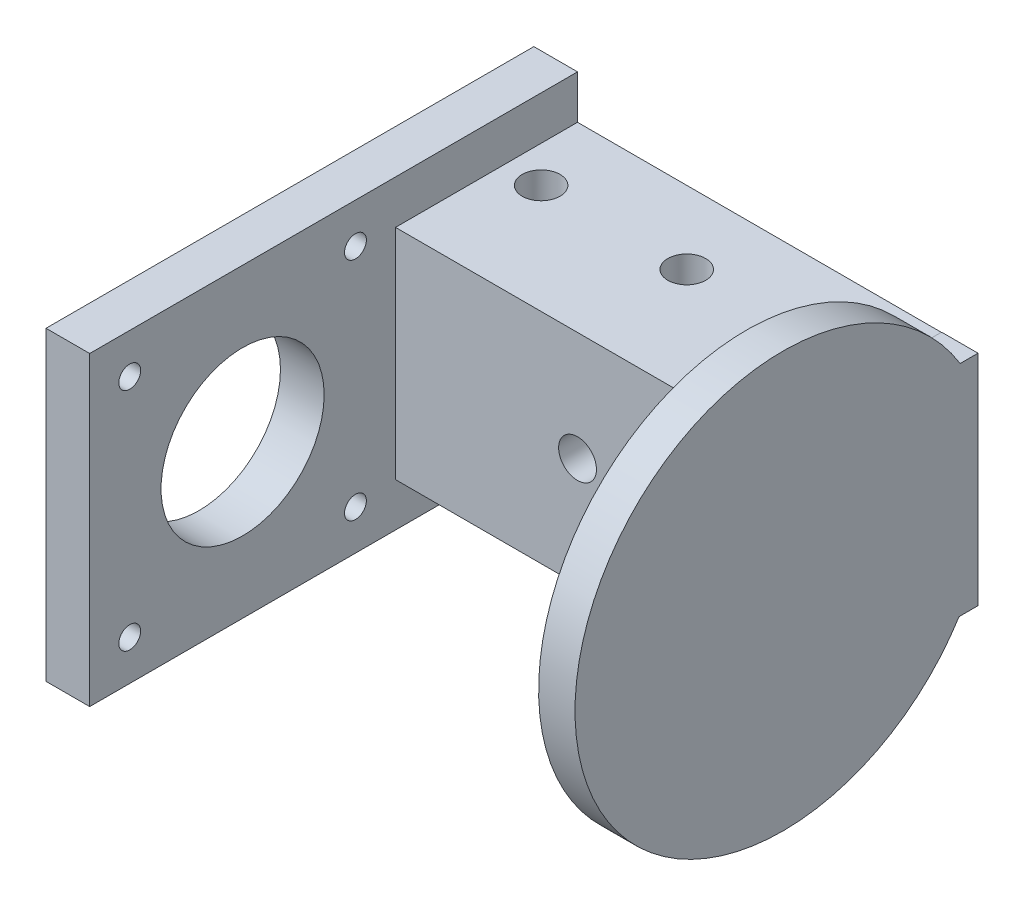
SolidWorks part; units mm, degrees
ref_plane "Front Plane" through (0, 0, 0) normal (0, 0, 1) x (1, 0, 0)
ref_plane "Top Plane" through (0, 0, 0) normal (0, 1, 0) x (1, 0, 0)
ref_plane "Right Plane" through (0, 0, 0) normal (1, 0, 0) x (0, 0, -1)
ref_plane "Plane1" through (45.0281, 0, 0) normal (1, 0, 0) x (0, 0, -1)
sketch "Sketch1" plane through (45.0281, 0, 0) normal (1, 0, 0) x (0, 0, -1)
  line L0 (-47, 0) -> (20, 0)
  line L1 (20, 0) -> (20, 42)
  line L2 (20, 42) -> (-47, 42)
  line L3 (-47, 42) -> (-47, 0)
  dimension "D1" = 67
  dimension "D2" = 42
  dimension "D3" = 20
extrude "Boss-Extrude1" add sketch "Sketch1" against normal blind 6
sketch "Sketch2" plane through (45.0281, 0, 0) normal (1, 0, 0) x (0, 0, -1)
  line L0 (20, 36) -> (20, 6)
  line L1 (20, 6) -> (-5, 6)
  line L2 (-5, 6) -> (-5, 36)
  line L3 (-5, 36) -> (20, 36)
  dimension "D1" = 25
extrude "Boss-Extrude2" add sketch "Sketch2" along normal blind 50
sketch "Sketch3" plane through (39.0281, 0, 0) normal (-1, 0, 0) x (0, 0, 1)
  line L0 (-20, 31) -> (-20, 11)
  line L1 (-20, 11) -> (0, 11)
  line L2 (0, 11) -> (0, 31)
  line L3 (0, 31) -> (-20, 31)
extrude "Cut-Extrude1" cut sketch "Sketch3" against normal through all
sketch "Sketch14" plane through (45.0281, 0, 0) normal (1, 0, 0) x (0, 0, -1)
  line L0 (-5, 36) -> (-5, 6) construction
  line L1 (-47, 21) -> (-5, 21) construction
  line L2 (-47, 42) -> (-47, 0) construction
  circle A2 centre (-26, 21) radius 11.2
  dimension "D1" = 22.4
  dimension "D2" = 21
extrude "Cut-Extrude12" cut sketch "Sketch14" against normal blind 10
sketch "Sketch15" plane through (0, 6, 0) normal (0, -1, 0) x (-1, 0, 0)
  line L0 (-95.0281, 20) -> (-45.0281, 20) construction
  line L1 (-45.0281, -5) -> (-45.0281, 20) construction
  circle A0 centre (-50.0281, 10) radius 2.6
  circle A1 centre (-70.0281, 10) radius 2.6
  dimension "D1" = 5.2
  dimension "D2" = 10
  dimension "D5" = 20
  dimension "D3" = 5
  dimension "D4" = 2
extrude "Cut-Extrude13" cut sketch "Sketch15" against normal through all
sketch "Sketch18" plane through (45.0281, 0, 0) normal (1, 0, 0) x (0, 0, -1)
  circle A0 centre (-10.5, 36.5) radius 1.5 construction
  circle A1 centre (-10.5, 5.5) radius 1.5 construction
  circle A2 centre (-41.5, 5.5) radius 1.5 construction
  circle A3 centre (-41.5, 36.5) radius 1.5 construction
  circle A4 centre (-10.5, 36.5) radius 1.5
  circle A5 centre (-10.5, 5.5) radius 1.5
  circle A6 centre (-41.5, 5.5) radius 1.5
  circle A7 centre (-41.5, 36.5) radius 1.5
extrude "Cut-Extrude14" cut sketch "Sketch18" against normal through all
sketch "Sketch19" plane through (0, 0, 5) normal (0, 0, 1) x (1, 0, 0)
  line L0 (70.0281, 36) -> (70.0281, 6) construction
  line L1 (95.0281, 36) -> (45.0281, 36) construction
  line L2 (95.0281, 6) -> (45.0281, 6) construction
  line L3 (95.0281, 21) -> (45.0281, 21) construction
  line L4 (95.0281, 36) -> (95.0281, 6) construction
  line L5 (45.0281, 36) -> (45.0281, 6) construction
  circle A0 centre (70.0281, 21) radius 2.6
  dimension "D1" = 5.2
extrude "Cut-Extrude15" cut sketch "Sketch19" against normal through all
sketch "Sketch20" plane through (95.0281, 0, 0) normal (1, 0, 0) x (0, 0, -1)
  circle A0 centre (-6.8021, 21.1403) radius 28.5431
extrude "Boss-Extrude3" add sketch "Sketch20" along normal blind 5
ref_plane "Plane2" through (0, 0, -20) normal (0, 0, -1) x (0, 1, 0)
sketch "Sketch21" plane through (0, 0, -20) normal (0, 0, -1) x (0, 1, 0)
  line L0 (49.6834, 100.0281) -> (-7.4028, 100.0281) construction
  line L1 (6, 95.0281) -> (36.0365, 95.0281)
  line L2 (6, 95.0281) -> (6, 100.0281)
  line L3 (6, 100.0281) -> (36.0365, 100.0281)
  line L4 (36.0365, 95.0281) -> (36.0365, 100.0281)
extrude "Boss-Extrude4" add sketch "Sketch21" against normal up to body
sketch "Sketch22" plane through (100.0281, 0, 0) normal (1, 0, 0) x (0, 0, -1)
  line L0 (20, -31.3974) -> (20, 31.3974) construction
  line L1 (20, 35.9418) -> (28.0746, 35.9418)
  line L2 (20, 35.9418) -> (20, 5.9985)
  line L3 (20, 5.9985) -> (28.0746, 5.9985)
  line L4 (28.0746, 35.9418) -> (28.0746, 5.9985)
extrude "Cut-Extrude16" cut sketch "Sketch22" against normal blind 10
